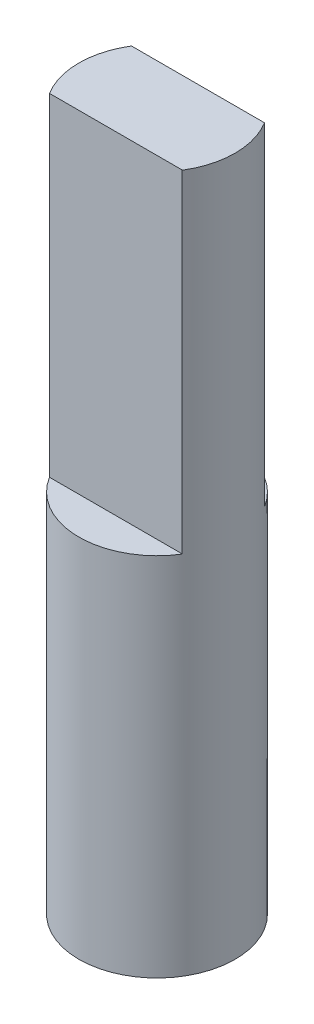
SolidWorks part; units mm, degrees
ref_plane "정면" through (0, 0, 0) normal (0, 0, 1) x (1, 0, 0)
ref_plane "윗면" through (0, 0, 0) normal (0, 1, 0) x (1, 0, 0)
ref_plane "우측면" through (0, 0, 0) normal (1, 0, 0) x (0, 0, -1)
sketch "스케치1" plane through (0, 0, 0) normal (0, 1, 0) x (1, 0, 0)
  circle A0 centre (0, 0) radius 2.35
  dimension "D1" = 4.7
extrude "보스-돌출1" add sketch "스케치1" along normal blind 21
ref_plane "평면1" through (0, 21, 0) normal (0, 1, 0) x (1, 0, 0)
sketch "스케치2" plane through (0, 21, 0) normal (0, 1, 0) x (1, 0, 0)
  line L1 (-2.0036, 1.2339) -> (1.9964, 1.2339)
  line L2 (-2.0036, 1.2339) -> (-2.0036, 2.4671)
  line L3 (-2.0036, 2.4671) -> (1.9964, 2.4671)
  line L4 (1.9964, 1.2339) -> (1.9964, 2.4671)
  line L5 (-2.0036, 1.2339) -> (1.9964, 1.2339)
  line L6 (-2.0036, -1.2339) -> (1.9964, -1.2339)
  line L7 (1.9964, -1.2339) -> (-2.0036, -1.2339)
  line L8 (1.9964, -1.2339) -> (1.9964, -2.4383)
  line L9 (1.9964, -2.4383) -> (-2.0036, -2.4383)
  line L10 (-2.0036, -1.2339) -> (-2.0036, -2.4383)
  point P16 (-0.0036, 1.2339)
  dimension "D2" = 4
  dimension "D3" = 4
extrude "컷-돌출6" cut sketch "스케치2" against normal blind 10 contours L1 L4 L3 L2 | L6 L10 L9 L8
